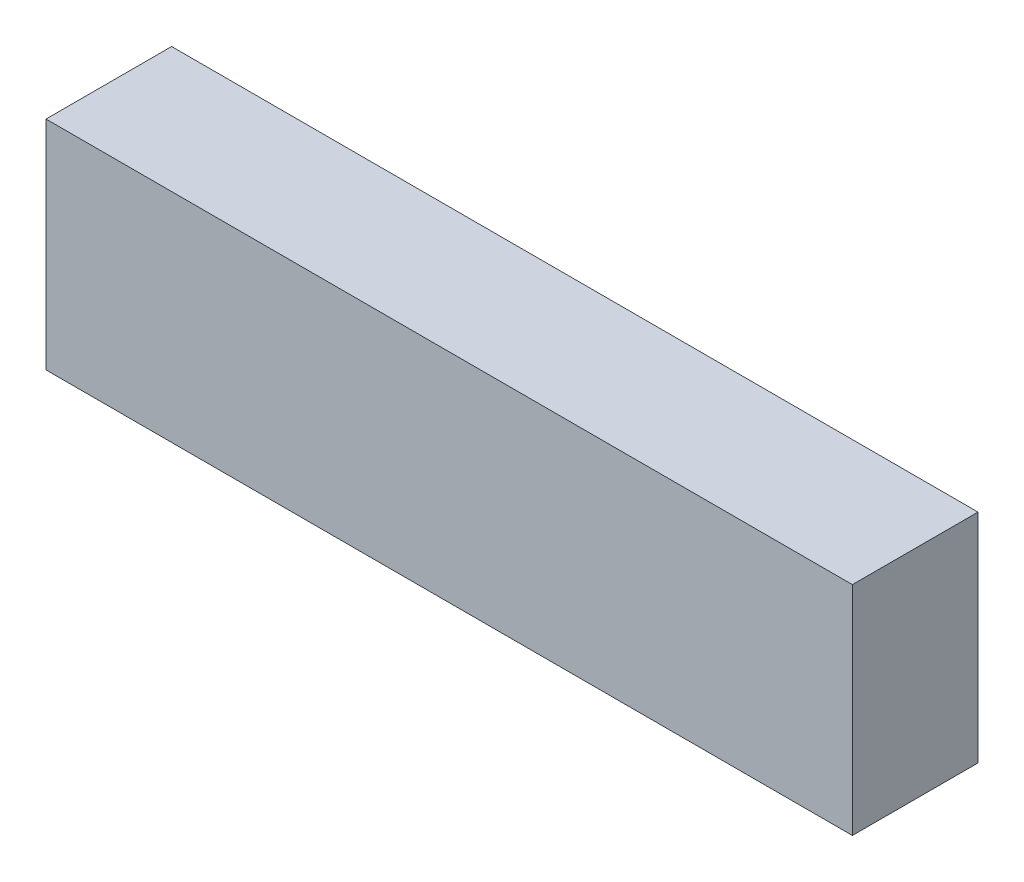
SolidWorks part; units mm, degrees
ref_plane "Front Plane" through (0, 0, 0) normal (0, 0, 1) x (1, 0, 0)
ref_plane "Top Plane" through (0, 0, 0) normal (0, 1, 0) x (1, 0, 0)
ref_plane "Right Plane" through (0, 0, 0) normal (1, 0, 0) x (0, 0, -1)
sketch "Sketch1" plane through (0, 0, 0) normal (0, 0, 1) x (1, 0, 0)
  line L0 (-79.2368, 46.33) -> (-32.2955, 46.33) construction
  line L1 (-79.0368, 46.13) -> (-32.4955, 46.13)
  line L2 (-79.0368, 46.13) -> (-79.0368, 33.59)
  line L3 (-79.0368, 33.59) -> (-32.4955, 33.59)
  line L4 (-32.4955, 46.13) -> (-32.4955, 33.59)
  line L5 (-32.2955, 46.33) -> (-32.2955, 33.39) construction
  line L6 (-32.2955, 33.39) -> (-79.2368, 33.39) construction
  line L7 (-79.2368, 46.33) -> (-79.2368, 33.39) construction
  dimension "D1" = 0.2
  dimension "D2" = 0.2
  dimension "D3" = 0.2
  dimension "D4" = 0.2
extrude "Boss-Extrude1" add sketch "Sketch1" along normal blind 7.25
shell "Shell1" thickness 0.5
equation "\"D1@Sketch1\"=0.2"
equation "\"D2@Sketch1\"=\"D1@Sketch1\""
equation "\"D3@Sketch1\"=\"D1@Sketch1\""
equation "\"D4@Sketch1\"=\"D1@Sketch1\""
